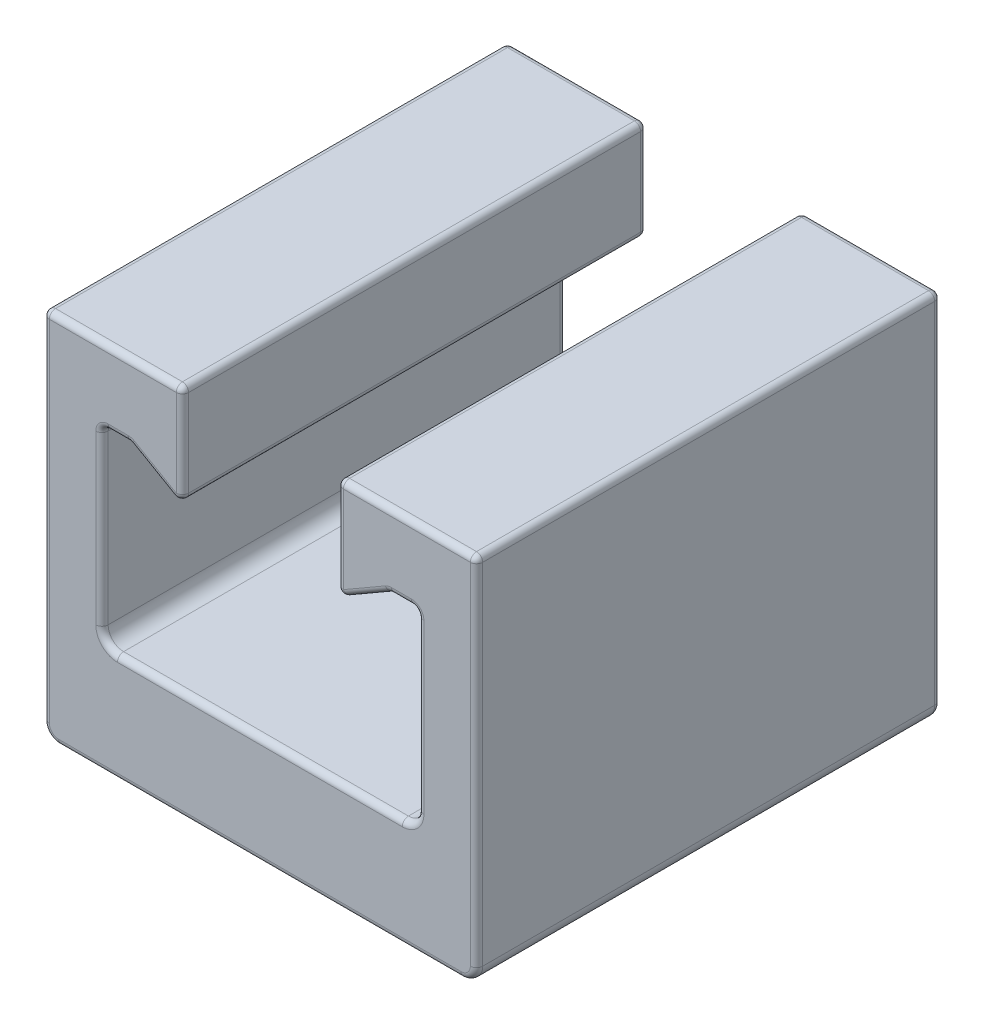
SolidWorks part; units mm, degrees
ref_plane "Front Plane" through (0, 0, 0) normal (0, 0, 1) x (1, 0, 0)
ref_plane "Top Plane" through (0, 0, 0) normal (0, 1, 0) x (1, 0, 0)
ref_plane "Right Plane" through (0, 0, 0) normal (1, 0, 0) x (0, 0, -1)
sketch "Sketch1" plane through (0, 0, 0) normal (0, 0, 1) x (1, 0, 0)
  line L0 (-4.5, 7.8989) -> (-7, 7.8989)
  line L1 (2.8395, 0) -> (-2.8395, 0)
  line L2 (-7, 7.8989) -> (-7, -4.1011)
  line L3 (2.8395, 0) -> (4.5, 0)
  line L4 (-7, -4.1011) -> (7, -4.1011)
  line L5 (-4.5, 0) -> (-2.8395, 0)
  line L6 (4.5, 0) -> (4.5, 5)
  line L7 (4.5, 5) -> (1.9, 3.4989)
  line L8 (-1.9, 3.4989) -> (-1.9, 8.4989)
  line L9 (4.5, 8.4989) -> (4.5, 5)
  line L10 (-4.5, 0) -> (-4.5, 5)
  line L11 (-4.5, 5) -> (-4.5, 8.4989)
  line L12 (1.9, 3.4989) -> (1.9, 8.4989)
  line L13 (-1.9, 8.4989) -> (-4.5, 8.4989)
  line L14 (-4.5, 5) -> (-1.9, 3.4989)
  line L15 (1.9, 8.4989) -> (4.5, 8.4989)
  line L16 (7, -4.1011) -> (7, 7.8989)
  line L17 (4.5, 7.8989) -> (7, 7.8989)
  line L18 (-4.2, 5.5196) -> (-2.5, 4.5381)
  line L19 (-2.5, 4.5381) -> (-2.5, 7.8989)
  line L20 (-2.5, 7.8989) -> (-4.5, 7.8989)
  line L21 (4.2, 5.5196) -> (2.5, 4.5381)
  line L22 (2.5, 4.5381) -> (2.5, 7.8989)
  line L23 (2.5, 7.8989) -> (4.5, 7.8989)
  line L24 (-4.2, 5.5196) -> (-5.1, 5.5196)
  line L25 (-5.1, 5.5196) -> (-5.1, -0.6)
  line L26 (-5.1, -0.6) -> (5.1, -0.6)
  line L27 (5.1, -0.6) -> (5.1, 5.5196)
  line L28 (5.1, 5.5196) -> (4.2, 5.5196)
  line L29 (-2.5, 7.8989) -> (2.5, 7.8989)
  dimension "D1" = 5
  dimension "D2" = 9
  dimension "D3" = 5
  dimension "D4" = 60
  dimension "D5" = 2.6
  dimension "D6" = 12
  dimension "D7" = 2.5
  dimension "D10" = 0.6
  dimension "D11" = 0.6
  dimension "D12" = 0.6
  dimension "D8" = 0.6
  dimension "D9" = 0.6
extrude "Boss-Extrude1" add sketch "Sketch1" along normal blind 15 contours L28 L27 L26 L25 L24 L11 L0 L2 L4 L16 L17 L9 | L24 L18 L19 L20 L11 | L28 L9 L23 L22 L21
fillet "Fillet1" radius 0.2 10 edges at (5.1, 5.5196, 7.5) (4.2, 5.5196, 7.5) (-4.2, 5.5196, 7.5) (-5.1, 5.5196, 7.5) (-7, 7.8989, 7.5) (7, 7.8989, 7.5) (2.5, 7.8989, 7.5) (-2.5, 7.8989, 7.5) (-2.5, 4.5381, 7.5) (2.5, 4.5381, 7.5)
fillet "Fillet2" radius 0.5 4 edges at (-7, -4.1011, 7.5) (7, -4.1011, 7.5) (-5.1, -0.6, 7.5) (5.1, -0.6, 7.5)
fillet "Fillet3" radius 0.2 56 edges at (6.8536, -3.9547, 15) (6.8536, -3.9547, 0) (7, 2.0489, 15) (7, 2.0489, 0) (6.9414, 7.8403, 15) (6.9414, 7.8403, 0) (4.75, 7.8989, 15) (4.75, 7.8989, 0) (2.5586, 7.8403, 15) (2.5586, 7.8403, 0) (2.5, 6.2917, 15) (2.5, 6.2917, 0) (2.6, 4.7113, 15) (2.6, 4.7113, 0) (3.4768, 5.1021, 0) (3.4768, 5.1021, 15) (4.2018, 5.5128, 15) (4.2018, 5.5128, 0) (4.5768, 5.5196, 0) (4.5768, 5.5196, 15) (5.0414, 5.461, 15) (5.0414, 5.461, 0) (5.1, 2.6098, 0) (5.1, 2.6098, 15) (4.9536, -0.4536, 15) (4.9536, -0.4536, 0) (0, -0.6, 0) (0, -0.6, 15) (-4.9536, -0.4536, 15) (-4.9536, -0.4536, 0) (-5.1, 2.6098, 15) (-5.1, 2.6098, 0) (-5.0414, 5.461, 15) (-5.0414, 5.461, 0) (-4.5768, 5.5196, 0) (-4.5768, 5.5196, 15) (-4.2018, 5.5128, 15) (-4.2018, 5.5128, 0) (-3.4768, 5.1021, 15) (-3.4768, 5.1021, 0) (-2.6, 4.7113, 15) (-2.6, 4.7113, 0) (-2.5, 6.2917, 0) (-2.5, 6.2917, 15) (-2.5586, 7.8403, 15) (-2.5586, 7.8403, 0) (-4.75, 7.8989, 0) (-4.75, 7.8989, 15) (-6.9414, 7.8403, 15) (-6.9414, 7.8403, 0) (-7, 2.0489, 0) (-7, 2.0489, 15) (-6.8536, -3.9547, 15) (-6.8536, -3.9547, 0) (0, -4.1011, 15) (0, -4.1011, 0)
